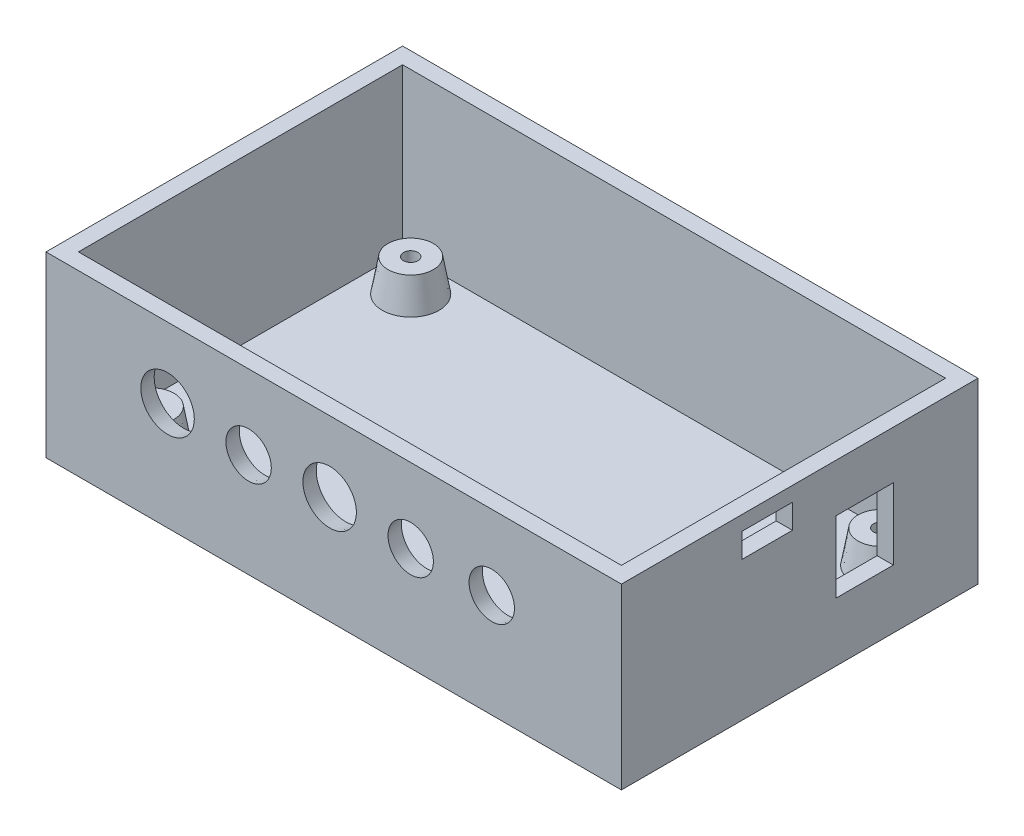
SolidWorks part; units mm, degrees
ref_plane "Front Plane" through (0, 0, 0) normal (0, 0, 1) x (1, 0, 0)
ref_plane "Top Plane" through (0, 0, 0) normal (0, 1, 0) x (1, 0, 0)
ref_plane "Right Plane" through (0, 0, 0) normal (1, 0, 0) x (0, 0, -1)
sketch "Sketch1" plane through (0, 0, 0) normal (0, 1, 0) x (1, 0, 0)
  line L1 (-45.085, 27.94) -> (45.085, 27.94)
  line L2 (-45.085, 27.94) -> (-45.085, -27.94)
  line L3 (-45.085, -27.94) -> (45.085, -27.94)
  line L4 (45.085, 27.94) -> (45.085, -27.94)
  line L5 (-45.085, 27.94) -> (45.085, -27.94) construction
  line L6 (-45.085, -27.94) -> (45.085, 27.94) construction
  point P0 (0, 0)
  dimension "D1" = 55.88
  dimension "D2" = 90.17
extrude "Boss-Extrude1" add sketch "Sketch1" along normal blind 27.94
shell "Shell1" thickness 2.54
sketch "Sketch2" plane through (0, 2.54, 0) normal (0, 1, 0) x (1, 0, 0)
  line L0 (0, 0) -> (55.0611, 0) construction
  line L1 (42.545, 25.4) -> (37.465, 20.32) construction
  line L2 (42.545, 25.4) -> (-42.545, 25.4) construction
  line L4 (0.635, 0) -> (0.635, 36.1762) construction
  circle A0 centre (37.465, 20.32) radius 4.445
  circle A2 centre (37.465, -20.32) radius 4.445
  circle A3 centre (-36.195, -20.32) radius 4.445
  circle A4 centre (-36.195, 20.32) radius 4.445
  dimension "D3" = 36.83
  dimension "D2" = 8.89
  dimension "D1" = 45
extrude "Boss-Extrude4" add sketch "Sketch2" along normal blind 5.08 draft 10
hole_wizard "Tap Drill for #4-40 Tap1" positions "Sketch4" profile "Sketch5" hole size "#4-40" standard "ANSI Inch"
sketch "Sketch4" plane through (0, 7.62, 0) normal (0, 1, 0) x (1, 0, 0)
  point P0 (-36.195, 20.32)
  point P3 (-36.195, -20.32)
  point P6 (37.465, -20.32)
  point P9 (37.465, 20.32)
sketch "Sketch5" plane through (-36.195, 7.62, -20.32) normal (1, 0, 0) x (0, 0, 1)
  line L0 (0, 0) -> (0, 7.0292)
  line L1 (0, 7.0292) -> (1.1303, 6.35)
  line L2 (1.1303, 6.35) -> (1.1303, 0)
  line L5 (1.1303, 0) -> (0, 0)
  line L10 (0, 7.0292) -> (-1.1303, 6.35) construction
  line L11 (0, -6.35) -> (0, 107.95) construction
  dimension "Hole Dia." = 2.2606
  dimension "Hole Depth" = 6.35
  dimension "Drill Angle" = 118
sketch "Sketch6" plane through (0, 0, 27.94) normal (0, 0, 1) x (1, 0, 0)
  line L0 (-36.195, 7.62) -> (37.465, 7.62) construction
  line L1 (-35.0647, 7.62) -> (-37.3253, 7.62) construction
  line L2 (41.0143, 7.62) -> (33.9157, 7.62) construction
  line L3 (24.765, 16.256) -> (-28.2519, 16.256) construction
  circle A0 centre (24.765, 16.256) radius 3.556
  circle A1 centre (12.065, 16.256) radius 3.556
  circle A2 centre (-13.335, 16.256) radius 3.556
  circle A3 centre (-0.635, 16.891) radius 4.191
  circle A4 centre (-26.035, 16.891) radius 4.191
  point P17 (-25.241, 16.891)
  dimension "D1" = 7.112
  dimension "D3" = 12.7
  dimension "D5" = 25.4
  dimension "D6" = 7.112
  dimension "D7" = 7.112
  dimension "D8" = 8.382
  dimension "D9" = 9.271
  dimension "D10" = 38.1
  dimension "D11" = 8.382
  dimension "D12" = 25.4
  dimension "D2" = 8.636
  dimension "D4" = 12.7
extrude "Cut-Extrude1" cut sketch "Sketch6" against normal up to next (2.54 mm away) draft 10 draft outward yes
sketch "Sketch7" plane through (45.085, 0, 0) normal (1, 0, 0) x (0, 0, -1)
  line L0 (23.8693, 7.62) -> (16.7707, 7.62) construction
  line L1 (5.6515, 9.2202) -> (14.6685, 9.2202)
  line L2 (5.6515, 9.2202) -> (5.6515, 20.3962)
  line L3 (5.6515, 20.3962) -> (14.6685, 20.3962)
  line L4 (14.6685, 9.2202) -> (14.6685, 20.3962)
  line L5 (5.6515, 9.2202) -> (14.6685, 20.3962) construction
  line L6 (5.6515, 20.3962) -> (14.6685, 9.2202) construction
  line L7 (21.4503, 7.62) -> (19.1897, 7.62) construction
  line L9 (-16.7707, 7.62) -> (-23.8693, 7.62) construction
  line L10 (-9.017, 25.654) -> (-1.143, 25.654)
  line L11 (-9.017, 25.654) -> (-9.017, 21.844)
  line L12 (-9.017, 21.844) -> (-1.143, 21.844)
  line L13 (-1.143, 25.654) -> (-1.143, 21.844)
  line L14 (-9.017, 25.654) -> (-1.143, 21.844) construction
  line L15 (-9.017, 21.844) -> (-1.143, 25.654) construction
  point P0 (10.16, 14.8082)
  point P9 (20.32, 7.62)
  point P10 (-5.08, 23.749)
  point P15 (-20.32, 7.62)
  dimension "D1" = 9.017
  dimension "D2" = 11.176
  dimension "D3" = 1.6002
  dimension "D4" = 10.16
  dimension "D5" = 3.81
  dimension "D6" = 7.874
  dimension "D7" = 14.224
  dimension "D8" = 15.24
extrude "Cut-Extrude2" cut sketch "Sketch7" against normal up to next
